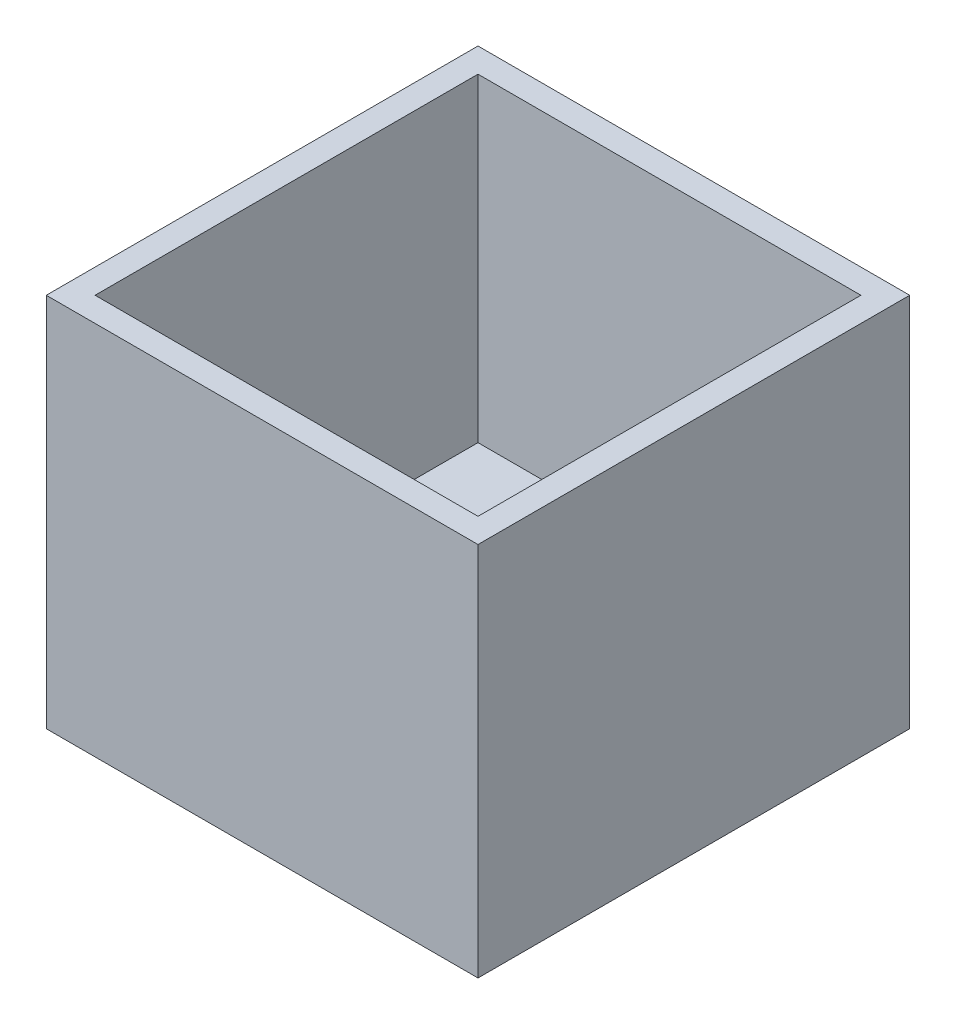
SolidWorks part; units mm, degrees
ref_plane "Front Plane" through (0, 0, 0) normal (0, 0, 1) x (1, 0, 0)
ref_plane "Top Plane" through (0, 0, 0) normal (0, 1, 0) x (1, 0, 0)
ref_plane "Right Plane" through (0, 0, 0) normal (1, 0, 0) x (0, 0, -1)
sketch "Sketch2" plane through (0, 0, 0) normal (0, 1, 0) x (1, 0, 0)
  line L1 (-11.5, -11.5) -> (11.5, -11.5)
  line L2 (-11.5, -11.5) -> (-11.5, 11.5)
  line L3 (-11.5, 11.5) -> (11.5, 11.5)
  line L4 (11.5, -11.5) -> (11.5, 11.5)
  line L5 (-11.5, -11.5) -> (11.5, 11.5) construction
  line L6 (-11.5, 11.5) -> (11.5, -11.5) construction
  point P0 (0, 0)
  dimension "D1" = 23
  dimension "D2" = 23
extrude "Boss-Extrude1" add sketch "Sketch2" along normal blind 20
sketch "Sketch3" plane through (0, 20, 0) normal (0, 1, 0) x (1, 0, 0)
  line L0 (-10.2, -10.2) -> (-10.2, 10.2)
  line L1 (-10, -10) -> (10, -10) construction
  line L2 (-10, -10) -> (-10, 10) construction
  line L3 (-10, 10) -> (10, 10) construction
  line L4 (10, -10) -> (10, 10) construction
  line L5 (-10, -10) -> (10, 10) construction
  line L6 (-10, 10) -> (10, -10) construction
  line L7 (-10.2, 10.2) -> (10.2, 10.2)
  line L8 (10.2, -10.2) -> (10.2, 10.2)
  line L9 (-10.2, -10.2) -> (10.2, -10.2)
  point P0 (0, 0)
  dimension "D1" = 20
  dimension "D2" = 20
  dimension "D3" = 0.2
extrude "Cut-Extrude1" cut sketch "Sketch3" against normal offset from surface (17 mm away) 3 up to face at (0, 0, 0)
